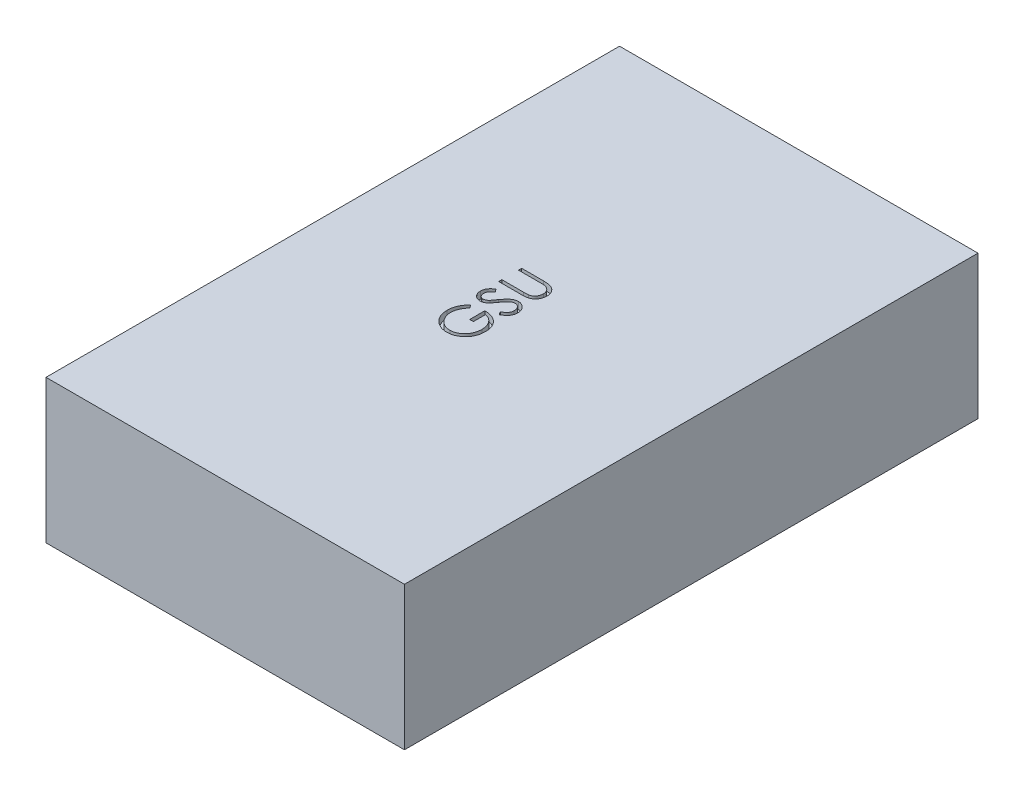
SolidWorks part; units mm, degrees
ref_plane "Front Plane" through (0, 0, 0) normal (0, 0, 1) x (1, 0, 0)
ref_plane "Top Plane" through (0, 0, 0) normal (0, 1, 0) x (1, 0, 0)
ref_plane "Right Plane" through (0, 0, 0) normal (1, 0, 0) x (0, 0, -1)
sketch "Sketch1" plane through (0, 0, 0) normal (0, 1, 0) x (1, 0, 0)
  line L1 (-50, 80) -> (50, 80)
  line L2 (-50, 80) -> (-50, -80)
  line L3 (-50, -80) -> (50, -80)
  line L4 (50, 80) -> (50, -80)
  line L5 (-50, 80) -> (50, -80) construction
  line L6 (-50, -80) -> (50, 80) construction
  point P0 (0, 0)
  dimension "D1" = 100
  dimension "D2" = 160
extrude "Boss-Extrude1" add sketch "Sketch1" along normal blind 40
sketch "Sketch2" plane through (0, 40, 0) normal (0, 1, 0) x (1, 0, 0)
  line L0 (0, -80) -> (0, 80) construction
  line L1 (-50, -80) -> (50, -80) construction
  line L2 (50, 80) -> (-50, 80) construction
  text T0 "GSU" font "Century Gothic" height 10
extrude "Cut-Extrude1" cut sketch "Sketch2" against normal blind 2
